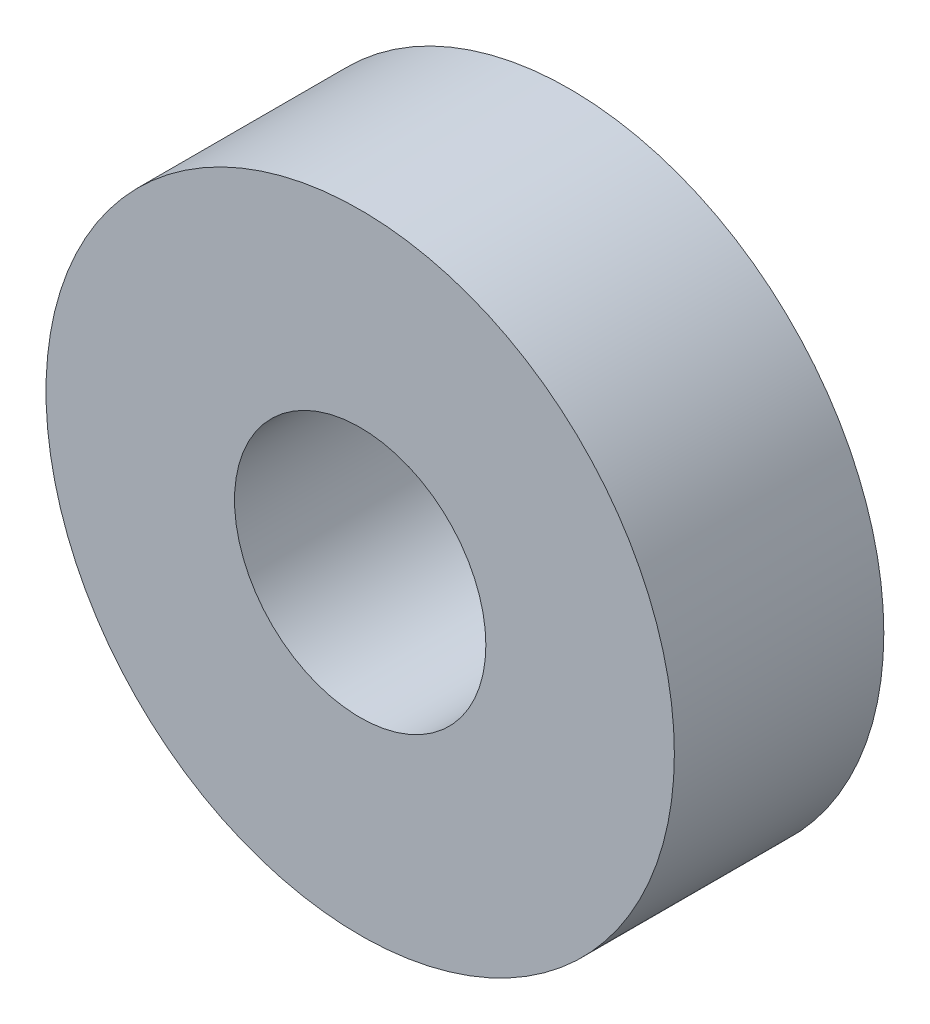
SolidWorks part; units mm, degrees
ref_plane "Front Plane" through (0, 0, 0) normal (0, 0, 1) x (1, 0, 0)
ref_plane "Top Plane" through (0, 0, 0) normal (0, 1, 0) x (1, 0, 0)
ref_plane "Right Plane" through (0, 0, 0) normal (1, 0, 0) x (0, 0, -1)
sketch "Sketch1" plane through (0, 0, 0) normal (0, 0, 1) x (1, 0, 0)
  circle A0 centre (0, 0) radius 25 construction
  circle A1 centre (0, 0) radius 15
  circle A2 centre (0, 0) radius 6
  dimension "D1" = 50
  dimension "D2" = 30
  dimension "D3" = 12
extrude "Boss-Extrude1" add sketch "Sketch1" along normal blind 10
